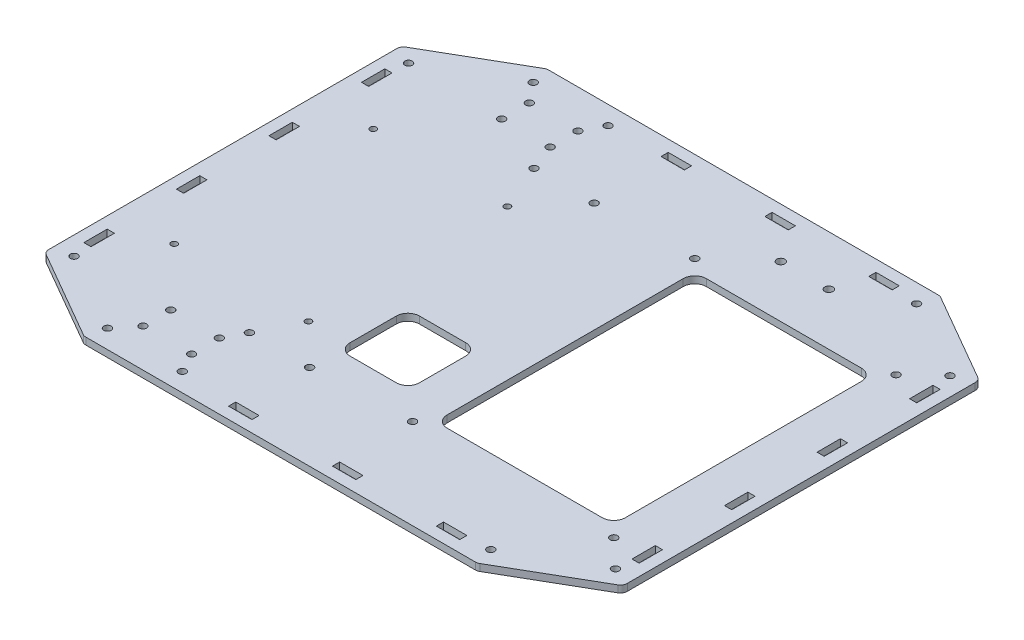
SolidWorks part; units mm, degrees
ref_plane "Front Plane" through (0, 0, 0) normal (0, 0, 1) x (1, 0, 0)
ref_plane "Top Plane" through (0, 0, 0) normal (0, 1, 0) x (1, 0, 0)
ref_plane "Right Plane" through (0, 0, 0) normal (1, 0, 0) x (0, 0, -1)
sketch "Sketch1" plane through (0, 0, 0) normal (0, 1, 0) x (1, 0, 0)
  line L0 (-85, 100) -> (85, 100)
  line L1 (-125, 100) -> (125, 100) construction
  line L2 (-125, 100) -> (-125, -100) construction
  line L3 (-125, -100) -> (125, -100) construction
  line L4 (125, 100) -> (125, -100) construction
  line L5 (85, 100) -> (125, 76.906)
  line L6 (125, 76.906) -> (125, -76.906)
  line L8 (-125, -76.906) -> (-125, 76.906)
  line L9 (-125, 76.906) -> (-85, 100)
  line L10 (-125, 0) -> (125, 0) construction
  line L11 (85, -100) -> (125, -76.906)
  line L12 (-85, -100) -> (85, -100)
  line L13 (-125, -76.906) -> (-85, -100)
  line L14 (0, 100) -> (0, -100) construction
  line L26 (-17.4, -91.9) -> (-27.5, -91.9)
  line L27 (-17.4, -91.9) -> (-17.4, -95)
  line L28 (-17.4, -95) -> (-27.5, -95)
  line L29 (-27.5, -91.9) -> (-27.5, -95)
  line L65 (-118.45, 14.95) -> (-118.45, -14.95) construction
  line L66 (-120, 65.05) -> (-116.9, 65.05)
  line L67 (-120, 65.05) -> (-120, 54.95)
  line L68 (-120, 54.95) -> (-116.9, 54.95)
  line L69 (-116.9, 65.05) -> (-116.9, 54.95)
  line L70 (-120, 25.05) -> (-116.9, 25.05)
  line L71 (-120, 25.05) -> (-120, 14.95)
  line L72 (-120, 14.95) -> (-116.9, 14.95)
  line L73 (-116.9, 25.05) -> (-116.9, 14.95)
  line L74 (-120, -14.95) -> (-116.9, -14.95)
  line L75 (-120, -14.95) -> (-120, -25.05)
  line L76 (-120, -25.05) -> (-116.9, -25.05)
  line L77 (-116.9, -14.95) -> (-116.9, -25.05)
  line L78 (-120, -54.95) -> (-116.9, -54.95)
  line L79 (-120, -54.95) -> (-120, -65.05)
  line L80 (-120, -65.05) -> (-116.9, -65.05)
  line L81 (-116.9, -54.95) -> (-116.9, -65.05)
  line L82 (120, -65.05) -> (116.9, -65.05)
  line L83 (116.9, -54.95) -> (116.9, -65.05)
  line L84 (120, -54.95) -> (116.9, -54.95)
  line L85 (120, -54.95) -> (120, -65.05)
  line L86 (120, -25.05) -> (116.9, -25.05)
  line L87 (116.9, -14.95) -> (116.9, -25.05)
  line L88 (120, -14.95) -> (116.9, -14.95)
  line L89 (120, -14.95) -> (120, -25.05)
  line L90 (120, 14.95) -> (116.9, 14.95)
  line L91 (116.9, 25.05) -> (116.9, 14.95)
  line L92 (120, 25.05) -> (116.9, 25.05)
  line L93 (120, 25.05) -> (120, 14.95)
  line L94 (120, 54.95) -> (116.9, 54.95)
  line L95 (116.9, 65.05) -> (116.9, 54.95)
  line L96 (120, 65.05) -> (116.9, 65.05)
  line L97 (120, 65.05) -> (120, 54.95)
  line L98 (27.5, -91.9) -> (27.5, -95)
  line L99 (27.5, -91.9) -> (17.4, -91.9)
  line L100 (17.4, -91.9) -> (17.4, -95)
  line L101 (27.5, -95) -> (17.4, -95)
  line L102 (72.4, -91.9) -> (72.4, -95)
  line L103 (72.4, -91.9) -> (62.3, -91.9)
  line L104 (62.3, -91.9) -> (62.3, -95)
  line L105 (72.4, -95) -> (62.3, -95)
  line L106 (72.4, 91.9) -> (62.3, 91.9)
  line L107 (62.3, 91.9) -> (62.3, 95)
  line L108 (72.4, 95) -> (62.3, 95)
  line L109 (72.4, 91.9) -> (72.4, 95)
  line L110 (27.5, 91.9) -> (17.4, 91.9)
  line L111 (17.4, 91.9) -> (17.4, 95)
  line L112 (27.5, 95) -> (17.4, 95)
  line L113 (27.5, 91.9) -> (27.5, 95)
  line L114 (-17.4, 95) -> (-27.5, 95)
  line L115 (-27.5, 91.9) -> (-27.5, 95)
  line L116 (-17.4, 91.9) -> (-27.5, 91.9)
  line L117 (-17.4, 91.9) -> (-17.4, 95)
  line L118 (-78.5, -69) -> (-78.5, -86) construction
  line L119 (-52.5, -69) -> (-78.5, -69) construction
  line L120 (-52.5, -86) -> (-52.5, -69) construction
  line L121 (-78.5, -86) -> (-52.5, -86) construction
  line L122 (-78.5, -69) -> (-78.5, -86) construction
  line L123 (-52.5, -69) -> (-78.5, -69) construction
  line L124 (-52.5, -86) -> (-52.5, -69) construction
  line L125 (-78.5, -86) -> (-52.5, -86) construction
  line L126 (-78.5, -77.5) -> (-52.5, -77.5) construction
  line L127 (-52.5, 86) -> (-52.5, 69) construction
  line L128 (-78.5, 86) -> (-52.5, 86) construction
  line L129 (-78.5, 69) -> (-78.5, 86) construction
  line L130 (-52.5, 69) -> (-78.5, 69) construction
  line L131 (-78.5, 77.5) -> (-52.5, 77.5) construction
  circle A0 centre (-50.5, -63) radius 1.6 construction
  circle A1 centre (82.8564, 92) radius 1.6 construction
  circle A2 centre (117, 72.2872) radius 1.6 construction
  circle A3 centre (117, -72.2872) radius 1.6 construction
  circle A4 centre (82.8564, -92) radius 1.6 construction
  circle A5 centre (-24.5, -63) radius 1.6 construction
  circle A6 centre (-24.5, 60) radius 1.6 construction
  circle A7 centre (-117, -72.2872) radius 1.6 construction
  circle A8 centre (-50.5, -92) radius 1.6 construction
  circle A9 centre (-50.5, 60) radius 1.6 construction
  circle A10 centre (-117, 72.2872) radius 1.6 construction
  circle A11 centre (-50.5, 92) radius 1.6 construction
  circle A12 centre (-50.5, -63) radius 1.6
  circle A13 centre (82.8564, 92) radius 1.6
  circle A14 centre (117, 72.2872) radius 1.6
  circle A15 centre (117, -72.2872) radius 1.6
  circle A16 centre (82.8564, -92) radius 1.6
  circle A17 centre (-24.5, -63) radius 1.6
  circle A18 centre (-24.5, 60) radius 1.6
  circle A19 centre (-117, -72.2872) radius 1.6
  circle A20 centre (-50.5, -92) radius 1.6
  circle A21 centre (-50.5, 60) radius 1.6
  circle A22 centre (-117, 72.2872) radius 1.6
  circle A23 centre (-50.5, 92) radius 1.6
  circle A24 centre (-82.8564, -92) radius 1.6 construction
  circle A25 centre (-82.8564, 92) radius 1.6 construction
  circle A26 centre (-82.8564, -92) radius 1.6
  circle A27 centre (-82.8564, 92) radius 1.6
  circle A28 centre (-55, -83.5) radius 1.59 construction
  circle A29 centre (-76, -83.5) radius 1.59 construction
  circle A30 centre (-55, -83.5) radius 1.59
  circle A31 centre (-76, -83.5) radius 1.59
  circle A32 centre (-55, -71.5) radius 1.59
  circle A33 centre (-76, -71.5) radius 1.59
  circle A34 centre (-55, 71.5) radius 1.59
  circle A35 centre (-55, 83.5) radius 1.59
  circle A36 centre (-76, 83.5) radius 1.59
  circle A37 centre (-76, 71.5) radius 1.59
  circle A39 centre (37.7074, 78.475) radius 1.75 construction
  circle A40 centre (58.4574, 78.475) radius 1.75 construction
  circle A41 centre (37.7074, 78.475) radius 1.75
  circle A42 centre (58.4574, 78.475) radius 1.75
  point P4 (0, 100)
  point P6 (-125, 0)
  point P9 (0, 0)
  point P20 (-22.45, -95)
  point P61 (-116.9, 60)
  point P62 (-116.9, 20)
  point P63 (-116.9, -20)
  point P64 (-116.9, -60)
  point P67 (-118.45, 0)
  dimension "D1" = 250
  dimension "D2" = 200
  dimension "D3" = 60
  dimension "D4" = 60
  dimension "D5" = 40
  dimension "D6" = 10.1
  dimension "D7" = 3.1
  dimension "D8" = 22.45
  dimension "D9" = 3
  dimension "D10" = 5
  dimension "D11" = 3.1
  dimension "D12" = 10.1
  dimension "D13" = 5
  dimension "D14" = 40
  dimension "D15" = 40
  dimension "D16" = 40
extrude "Boss-Extrude1" add sketch "Sketch1" along normal blind 3
sketch "Sketch3" plane through (0, 3, 0) normal (0, 1, 0) x (1, 0, 0)
  line L0 (28, 56) -> (95, 56)
  line L1 (18, 61) -> (105, 61) construction
  line L2 (18, 61) -> (18, -61) construction
  line L3 (18, -61) -> (105, -61) construction
  line L4 (105, 61) -> (105, -61) construction
  line L5 (100, 51) -> (100, -51)
  line L6 (28, -56) -> (95, -56)
  line L7 (23, 51) -> (23, -51)
  line L8 (23, 56) -> (100, 56) construction
  line L9 (23, 56) -> (23, -56) construction
  line L10 (23, -56) -> (100, -56) construction
  line L11 (100, 56) -> (100, -56) construction
  line L17 (-20, -50) -> (0, -50)
  line L18 (-25, -45) -> (-25, -25)
  line L19 (-20, -20) -> (0, -20)
  line L20 (5, -45) -> (5, -25)
  arc A0 (28, 56) -> (23, 51) centre (28, 51) ccw
  arc A1 (28, -56) -> (23, -51) centre (28, -51) cw
  arc A2 (100, -51) -> (95, -56) centre (95, -51) cw
  arc A3 (95, 56) -> (100, 51) centre (95, 51) cw
  arc A4 (-20, -50) -> (-25, -45) centre (-20, -45) cw
  arc A5 (0, -50) -> (5, -45) centre (0, -45) ccw
  arc A6 (0, -20) -> (5, -25) centre (0, -25) cw
  arc A7 (-25, -25) -> (-20, -20) centre (-20, -25) cw
  point P27 (-25, -50)
  point P32 (5, -20)
  point P35 (-25, -20)
  line B0 (-25, -50) -> (-104, -50) construction
  line B1 (-25, -50) -> (-25, 50) construction
  line B2 (-25, 50) -> (-104, 50) construction
  line B3 (-104, -50) -> (-104, 50) construction
  circle B4 centre (-100, -46) radius 1.35
  circle B5 centre (-42, -46) radius 1.35
  circle B6 centre (-42, 40) radius 1.35
  circle B7 centre (-100, 40) radius 1.35
  line B8 (14, 65) -> (14, -65) construction
  line B9 (14, 65) -> (109, 65) construction
  circle B10 centre (18, 61) radius 1.6
  circle B11 centre (105, 61) radius 1.6
  circle B12 centre (105, -61) radius 1.6
  circle B13 centre (18, -61) radius 1.6
  dimension "D4" = 5
  dimension "D5" = 5
  dimension "D7" = 5
  dimension "D1" = 25
  dimension "D2" = 14
  dimension "D6" = 30
  dimension "D3" = 5
sketch_block_instance "Block-Jetson-Nano-1"
sketch_block "Block-Jetson-Nano"
sketch_block_instance "Block-MCU-Board-1"
sketch_block "Block2" parameters "D3"=3.2, "D1"=87, "D2"=122
extrude "Cut-Extrude1" cut sketch "Sketch3" against normal up to next
fillet "Fillet1" radius 3 8 edges at (85, 1.5, -100) (125, 1.5, -76.906) (-85, 1.5, -100) (-125, 1.5, -76.906) (-85, 1.5, 100) (-125, 1.5, 76.906) (85, 1.5, 100) (125, 1.5, 76.906)
